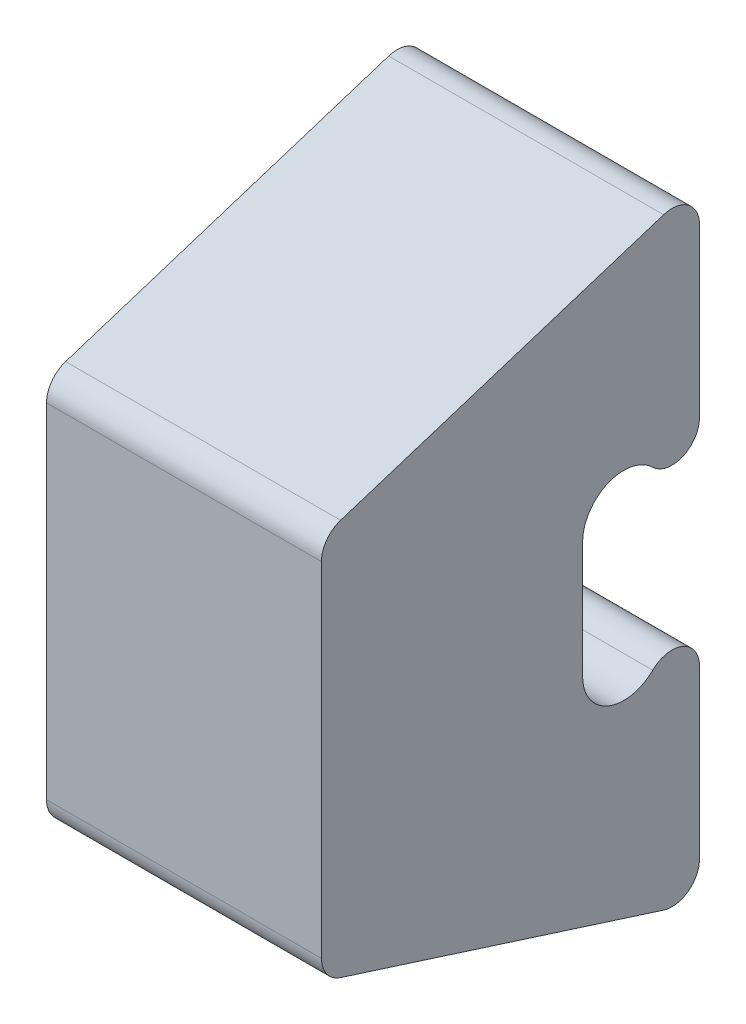
SolidWorks part; units mm, degrees
material "ABS"
ref_plane "Front Plane" through (0, 0, 0) normal (1, 0, 0) x (0, 1, 0)
ref_plane "Top Plane" through (0, 0, 0) normal (0, 0, 1) x (0, 1, 0)
ref_plane "Right Plane" through (0, 0, 0) normal (0, 1, 0) x (-1, 0, 0)
sketch "Sketch3" plane through (0, 0, 0) normal (1, 0, 0) x (0, 1, 0)
  line L12 (-4, 5.4) -> (-1.5642, 5.4)
  line L13 (-0.85, 7.1) -> (0.85, 7.1)
  line L14 (1.5642, 5.4) -> (4, 5.4)
  line L15 (4.3811, 5.9216) -> (2.8811, 10.6216)
  line L16 (2.5, 10.9) -> (-2.5, 10.9)
  line L17 (-2.8811, 10.6216) -> (-4.3811, 5.9216)
  line L18 (-4, 5.4) -> (-1.5642, 5.4)
  line L19 (-0.85, 7.1) -> (0.85, 7.1)
  line L20 (1.5642, 5.4) -> (4, 5.4)
  line L21 (4.3811, 5.9216) -> (2.8811, 10.6216)
  line L22 (2.5, 10.9) -> (-2.5, 10.9)
  line L23 (-2.8811, 10.6216) -> (-4.3811, 5.9216)
  arc A16 (-4.3811, 5.9216) -> (-4, 5.4) centre (-4, 5.8) ccw
  arc A17 (-1.5642, 5.4) -> (-1.2785, 6.08) centre (-1.5642, 5.8) ccw
  arc A18 (-0.85, 7.1) -> (-1.2785, 6.08) centre (-0.85, 6.5) ccw
  arc A19 (1.2785, 6.08) -> (0.85, 7.1) centre (0.85, 6.5) ccw
  arc A20 (1.2785, 6.08) -> (1.5642, 5.4) centre (1.5642, 5.8) ccw
  arc A21 (4, 5.4) -> (4.3811, 5.9216) centre (4, 5.8) ccw
  arc A22 (2.8811, 10.6216) -> (2.5, 10.9) centre (2.5, 10.5) ccw
  arc A23 (-2.5, 10.9) -> (-2.8811, 10.6216) centre (-2.5, 10.5) ccw
  arc A24 (-4.3811, 5.9216) -> (-4, 5.4) centre (-4, 5.8) ccw
  arc A25 (-1.5642, 5.4) -> (-1.2785, 6.08) centre (-1.5642, 5.8) ccw
  arc A26 (-0.85, 7.1) -> (-1.2785, 6.08) centre (-0.85, 6.5) ccw
  arc A27 (1.2785, 6.08) -> (0.85, 7.1) centre (0.85, 6.5) ccw
  arc A28 (1.2785, 6.08) -> (1.5642, 5.4) centre (1.5642, 5.8) ccw
  arc A29 (4, 5.4) -> (4.3811, 5.9216) centre (4, 5.8) ccw
  arc A30 (2.8811, 10.6216) -> (2.5, 10.9) centre (2.5, 10.5) ccw
  arc A31 (-2.5, 10.9) -> (-2.8811, 10.6216) centre (-2.5, 10.5) ccw
  dimension "D1" = 0.1
extrude "Boss-Extrude1" add sketch "Sketch3" along normal blind 1 and the other way blind 3
